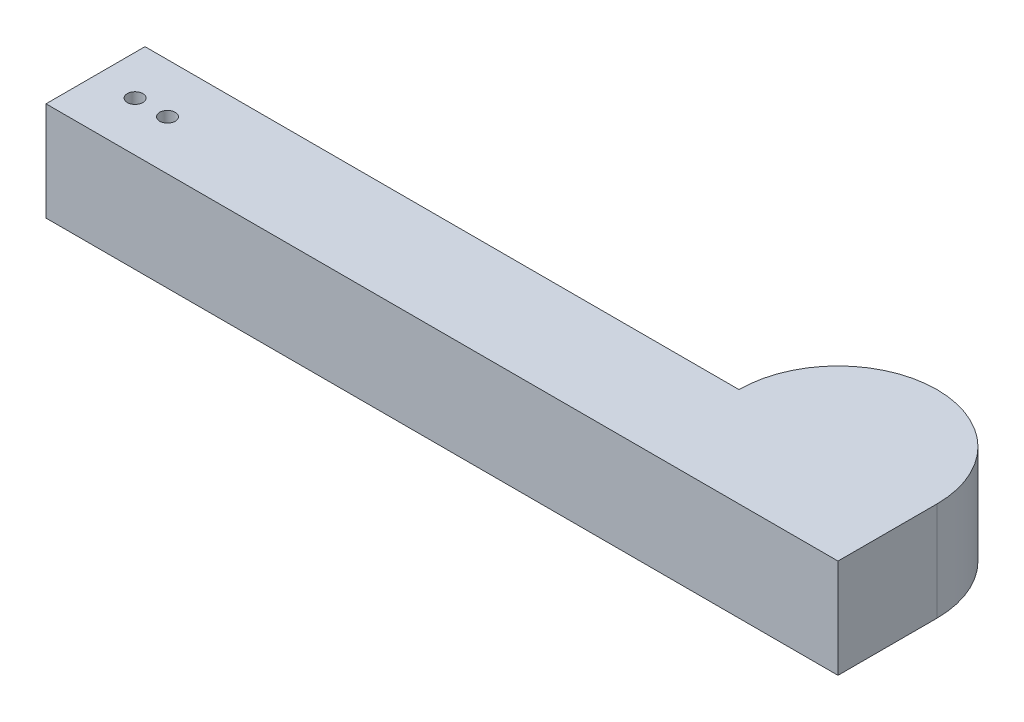
SolidWorks part; units mm, degrees
ref_plane "Front Plane" through (0, 0, 0) normal (0, 0, 1) x (1, 0, 0)
ref_plane "Top Plane" through (0, 0, 0) normal (0, 1, 0) x (1, 0, 0)
ref_plane "Right Plane" through (0, 0, 0) normal (1, 0, 0) x (0, 0, -1)
sketch "Sketch1" plane through (0, 0, 0) normal (0, 1, 0) x (1, 0, 0)
  line L1 (0, 0) -> (203.2, 0)
  line L2 (0, 0) -> (0, 25.4)
  line L3 (0, 25.4) -> (152.4, 25.4)
  line L4 (203.2, 0) -> (203.2, 25.4)
  arc A0 (203.2, 25.4) -> (152.4, 25.4) centre (177.8, 25.4) ccw
  dimension "D1" = 25.4
  dimension "D2" = 203.2
extrude "Boss-Extrude1" add sketch "Sketch1" along normal blind 25.4
sketch "Sketch2" plane through (0, 25.4, 0) normal (0, 1, 0) x (1, 0, 0)
  line L0 (0, 25.4) -> (0, 0) construction
  line L1 (0, 0) -> (203.2, 0) construction
  line L2 (152.4, 25.4) -> (0, 25.4) construction
  circle A0 centre (10.16, 12.7) radius 1.999
  circle A1 centre (18.4658, 12.7) radius 1.999
  point P2 (0, 12.7)
  dimension "D1" = 10.16
  dimension "D3" = 3.998
  dimension "D2" = 12.7
  dimension "D4" = 8.3058
  dimension "D5" = 12.7
extrude "Cut-Extrude1" cut sketch "Sketch2" against normal blind 25.4
